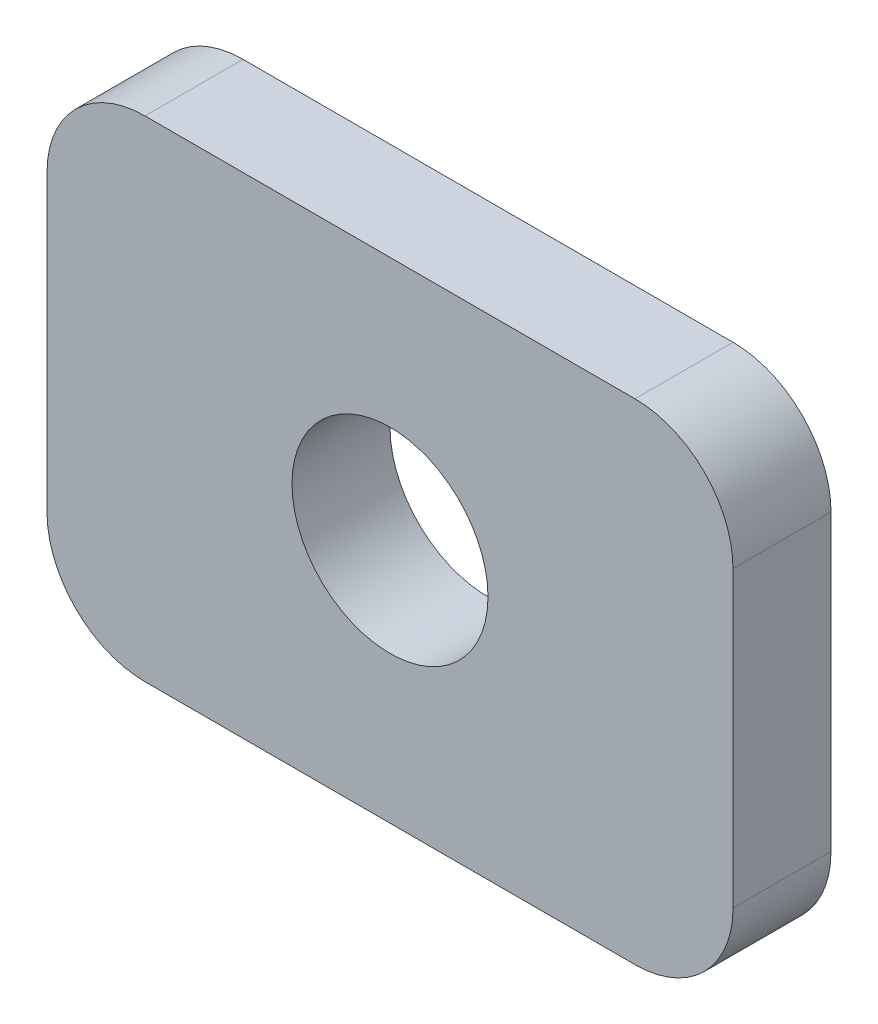
SolidWorks part; units mm, degrees
ref_plane "Спереди" through (0, 0, 0) normal (0, 0, 1) x (1, 0, 0)
ref_plane "Сверху" through (0, 0, 0) normal (0, 1, 0) x (1, 0, 0)
ref_plane "Справа" through (0, 0, 0) normal (1, 0, 0) x (0, 0, -1)
other "Configuration Table"
sketch "Эскиз1" plane through (0, 0, 0) normal (0, 0, 1) x (1, 0, 0)
  line L0 (35, -950) -> (35, 49050) construction
  line L1 (10, 0) -> (60, 0)
  line L2 (0, 10) -> (0, 40)
  line L3 (10, 50) -> (60, 50)
  line L4 (70, 10) -> (70, 40)
  line L5 (-1000, 25) -> (49000, 25) construction
  arc A0 (10, 0) -> (0, 10) centre (10, 10) cw
  arc A1 (0, 40) -> (10, 50) centre (10, 40) cw
  arc A2 (60, 50) -> (70, 40) centre (60, 40) cw
  arc A3 (60, 0) -> (70, 10) centre (60, 10) ccw
  circle A4 centre (35, 25) radius 10
  point P8 (35, 50)
  point P9 (35, 25)
  point P11 (0, 25)
  point P15 (0, 0)
  point P18 (0, 50)
  point P21 (70, 50)
  dimension "D3" = 10
  dimension "D1" = 50
  dimension "D2" = 70
extrude "Бобышка-Вытянуть1" add sketch "Эскиз1" along normal blind 10
